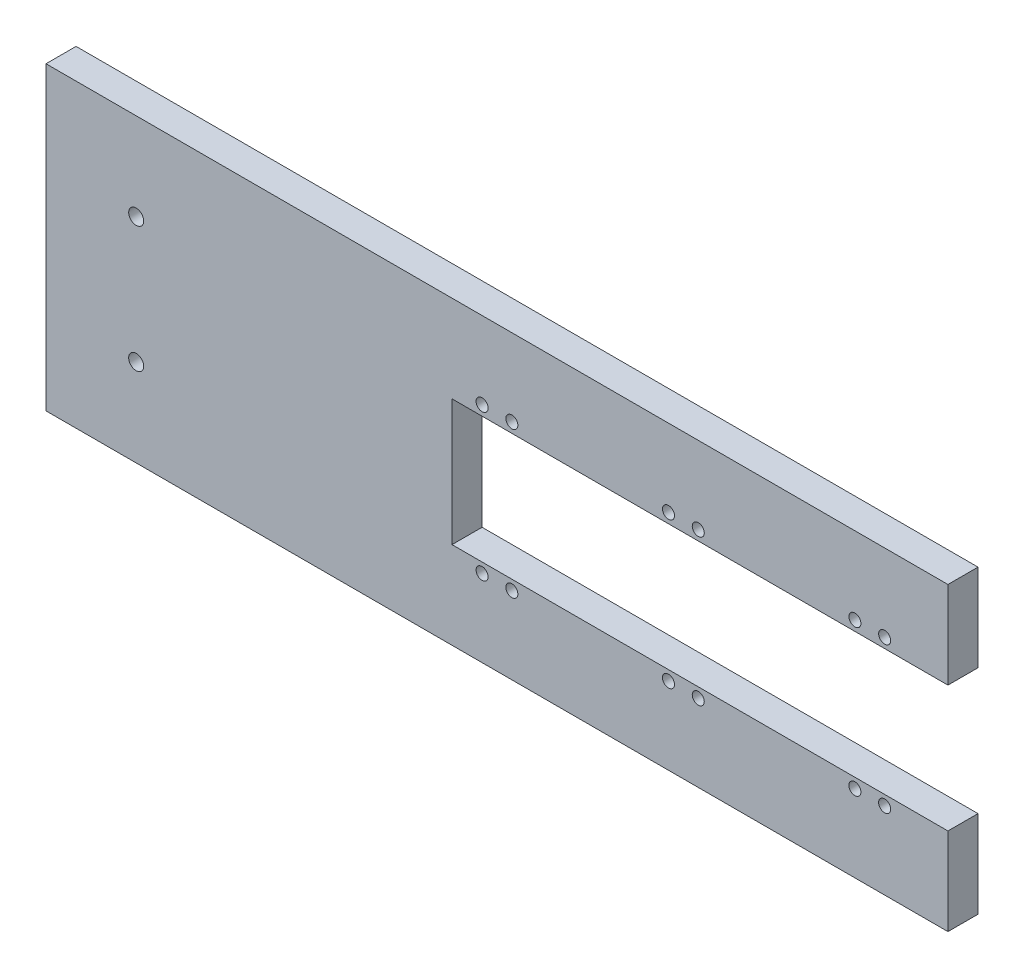
SolidWorks part; units mm, degrees
ref_plane "Front Plane" through (0, 0, 0) normal (0, 0, 1) x (1, 0, 0)
ref_plane "Top Plane" through (0, 0, 0) normal (0, 1, 0) x (1, 0, 0)
ref_plane "Right Plane" through (0, 0, 0) normal (1, 0, 0) x (0, 0, -1)
sketch "Sketch7" plane through (0, 0, 0) normal (0, 0, 1) x (1, 0, 0)
  line L0 (37.1626, 0) -> (172.6077, 0) construction
  line L1 (-150, 50) -> (150, 50)
  line L2 (-150, 50) -> (-150, -50)
  line L3 (-150, -50) -> (150, -50)
  line L4 (150, 50) -> (150, -50)
  point P7 (150, 0)
  dimension "D1" = 150
  dimension "D2" = 100
  dimension "D3" = 150
sketch "Sketch5" [suppressed] plane through (0, 0, 10) normal (0, 0, 1) x (1, 0, 0)
  line L0 (-20, 35) -> (-20, -35) construction
  line L1 (-20, 21.5) -> (11, 21.5)
  line L2 (-20, 21.5) -> (-20, -21.5)
  line L3 (-20, -21.5) -> (11, -21.5)
  line L4 (11, 21.5) -> (11, -21.5)
  line L5 (0, 0) -> (61.9749, 0) construction
  dimension "D1" = 43
  dimension "D2" = 11
extrude "Cut-Extrude1" [suppressed] cut sketch "Sketch5" against normal through all and the other way through all
extrude "Boss-Extrude1" add sketch "Sketch7" against normal blind 10
sketch "Sketch4" plane through (0, 0, 0) normal (0, 0, 1) x (1, 0, 0)
  line L0 (52.05, 27) -> (71.95, 27) construction
  line L1 (-9.95, -27) -> (9.95, -27) construction
  line L2 (-9.95, -27) -> (-9.95, 27) construction
  line L3 (-9.95, 27) -> (9.95, 27) construction
  line L4 (9.95, -27) -> (9.95, 27) construction
  line L5 (-9.95, -27) -> (9.95, 27) construction
  line L6 (-9.95, 27) -> (9.95, -27) construction
  line L7 (-20, -35) -> (20, -35) construction
  line L8 (-20, -35) -> (-20, 35) construction
  line L9 (-20, 35) -> (20, 35) construction
  line L10 (20, -35) -> (20, 35) construction
  line L11 (-20, -35) -> (20, 35) construction
  line L12 (-20, 35) -> (20, -35) construction
  line L13 (52.05, -27) -> (52.05, 27) construction
  line L14 (52.05, -27) -> (71.95, -27) construction
  line L15 (71.95, -27) -> (71.95, 27) construction
  line L16 (52.05, -27) -> (71.95, 27) construction
  line L17 (114.05, 27) -> (133.95, 27) construction
  line L18 (114.05, -27) -> (114.05, 27) construction
  line L19 (114.05, -27) -> (133.95, -27) construction
  line L20 (133.95, -27) -> (133.95, 27) construction
  line L21 (114.05, -27) -> (133.95, 27) construction
  point P0 (0, 0)
  point P6 (0, 0)
  dimension "D1" = 54
  dimension "D2" = 19.9
  dimension "D3" = 40
  dimension "D4" = 70
  dimension "D5" = 3
sketch "Sketch1" plane through (0, 0, 0) normal (0, 0, 1) x (1, 0, 0)
  line L0 (0, 0) -> (0, 19.8954) construction
  line L1 (0, 0) -> (16.2753, 0) construction
  line L3 (-20, -35) -> (20, -35) construction
  line L4 (-20, -35) -> (-20, 35) construction
  line L5 (-20, 35) -> (20, 35) construction
  line L6 (20, -35) -> (20, 35) construction
  line L7 (-20, -35) -> (20, 35) construction
  line L8 (-20, 35) -> (20, -35) construction
  circle A0 centre (4.95, -24.3) radius 2
  circle A1 centre (-4.95, -24.3) radius 2
  circle A2 centre (-4.95, 24.3) radius 2
  circle A3 centre (4.95, 24.3) radius 2
  dimension "D3" = 9.9
  dimension "D4" = 48.6
  dimension "D5" = 4
  dimension "D1" = 70
  dimension "D2" = 40
extrude "Cut-Extrude2" cut sketch "Sketch1" against normal through all
pattern_linear "LPattern1" count 4 spacing 62 along (1, 0, 0) of "Cut-Extrude2"
sketch "Sketch8" plane through (0, 0, 0) normal (0, 0, 1) x (1, 0, 0)
  line L0 (150, -50) -> (150, 50) construction
  line L1 (-14.95, 21) -> (150, 21)
  line L2 (-14.95, 21) -> (-14.95, -21)
  line L3 (-14.95, -21) -> (150, -21)
  line L4 (150, 21) -> (150, -21)
  line L6 (-55.093, 0) -> (-17.7872, 0) construction
  line L7 (-9.95, -27) -> (-9.95, 27) construction
  point P11 (-14.95, 0)
  dimension "D1" = 42
  dimension "D2" = 5
extrude "Cut-Extrude3" cut sketch "Sketch8" against normal through all
sketch "Sketch10" plane through (0, 0, 0) normal (0, 0, 1) x (1, 0, 0)
  line L0 (5.5, 0) -> (-5.5, 0) construction
  line L1 (0, -5.5) -> (0, 5.5) construction
  circle A0 centre (-120, 20.9311) radius 2.5
  circle A1 centre (-120, -20.9311) radius 2.5
  dimension "D1" = 5
  dimension "D2" = 120
extrude "Cut-Extrude4" cut sketch "Sketch10" against normal through all
